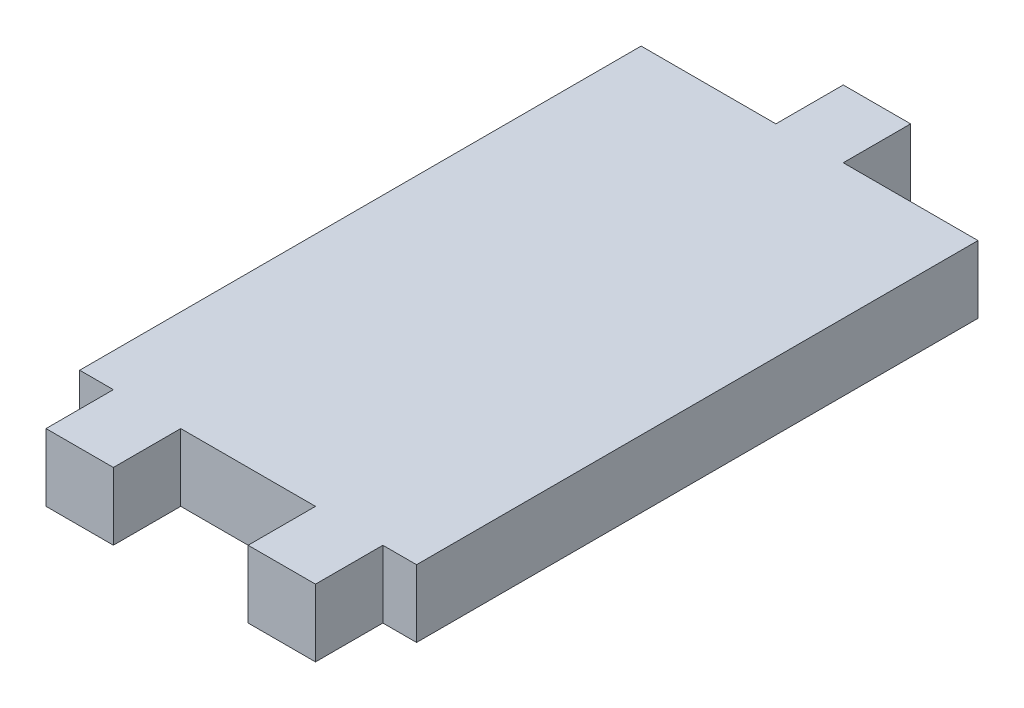
SolidWorks part; units mm, degrees
material "Maple"
ref_plane "Front Plane" through (0, 0, 0) normal (0, 0, 1) x (1, 0, 0)
ref_plane "Top Plane" through (0, 0, 0) normal (0, 1, 0) x (1, 0, 0)
ref_plane "Right Plane" through (0, 0, 0) normal (1, 0, 0) x (0, 0, -1)
sketch "Sketch1" plane through (0, 0, 0) normal (0, 1, 0) x (1, 0, 0)
  line L0 (0, 0) -> (0, 50)
  line L1 (0, 50) -> (-12, 50)
  line L2 (-30, 50) -> (-30, 0)
  line L3 (-30, 0) -> (-27, 0)
  line L4 (-12, 50) -> (-12, 56)
  line L5 (-12, 56) -> (-18, 56)
  line L6 (-18, 56) -> (-18, 50)
  line L7 (-27, 0) -> (-27, -6)
  line L8 (-27, -6) -> (-21, -6)
  line L9 (-21, -6) -> (-21, 0)
  line L10 (-3, 0) -> (-3, -6)
  line L11 (-3, -6) -> (-9, -6)
  line L12 (-9, -6) -> (-9, 0)
  line L13 (-3, 0) -> (0, 0)
  line L14 (-21, 0) -> (-9, 0)
  line L15 (-18, 50) -> (-30, 50)
  dimension "D1" = 50
  dimension "D2" = 30
  dimension "D3" = 6
  dimension "D4" = 6
  dimension "D5" = 12
  dimension "D6" = 6
  dimension "D7" = 6
  dimension "D8" = 3
  dimension "D9" = 6
  dimension "D10" = 3
extrude "Boss-Extrude1" add sketch "Sketch1" along normal blind 6
